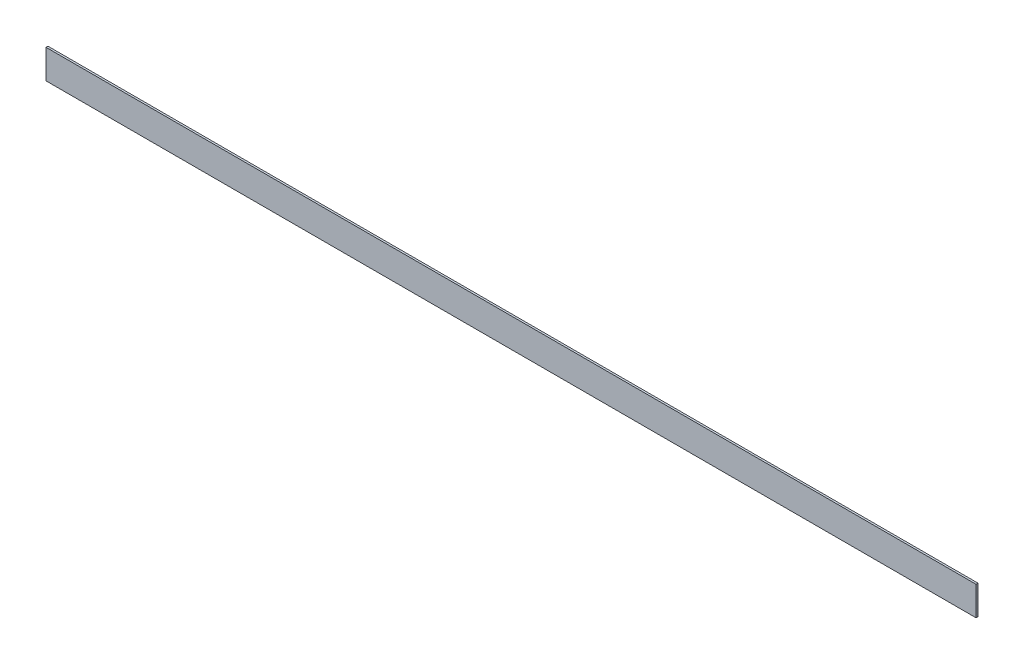
SolidWorks part; units mm, degrees
material "Silicon Rubber"
ref_plane "Front Plane" through (0, 0, 0) normal (0, 0, 1) x (1, 0, 0)
ref_plane "Top Plane" through (0, 0, 0) normal (0, 1, 0) x (1, 0, 0)
ref_plane "Right Plane" through (0, 0, 0) normal (1, 0, 0) x (0, 0, -1)
sketch "Sketch1" plane through (0, 0, 0) normal (0, 0, 1) x (1, 0, 0)
  line L1 (0, 0) -> (609.6, 0)
  line L2 (0, 0) -> (0, 19.05)
  line L3 (0, 19.05) -> (609.6, 19.05)
  line L4 (609.6, 0) -> (609.6, 19.05)
  dimension "D1" = 609.6
  dimension "D2" = 19.05
extrude "Boss-Extrude1" add sketch "Sketch1" along normal blind 1.27
ref_plane "Plane1" through (0, 9.525, 0) normal (0, 1, 0) x (1, 0, 0)
